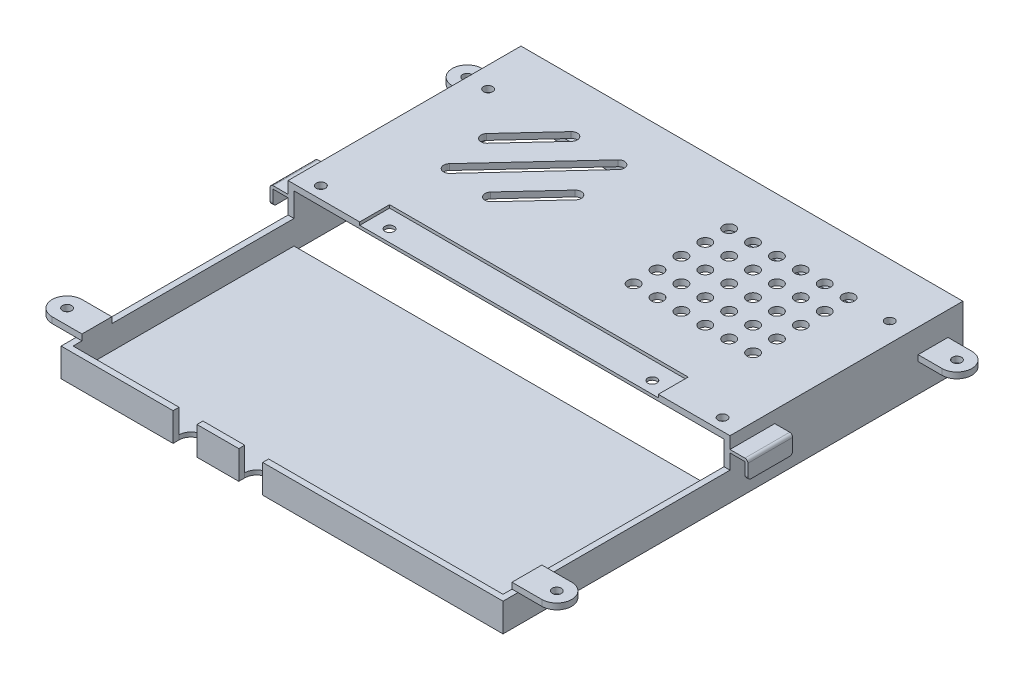
SolidWorks part; units mm, degrees
material "PET"
ref_plane "前视基准面" through (0, 0, 0) normal (0, 0, 1) x (1, 0, 0)
ref_plane "上视基准面" through (0, 0, 0) normal (0, 1, 0) x (1, 0, 0)
ref_plane "右视基准面" through (0, 0, 0) normal (1, 0, 0) x (0, 0, -1)
other "边界框"
ref_plane "Default Plane" through (-13, 0, 0) normal (0, 0, -1) x (-1, 0, 0)
other "Configuration Table"
sketch "草图1" plane through (0, 0, 0) normal (1, 0, 0) x (0, 0, -1)
  line L0 (0, 0) -> (154, 0)
  line L1 (0, 0) -> (0, 9.5)
  line L2 (0, 9.5) -> (76, 9.5)
  line L3 (76, 9.5) -> (76, 19.5)
  line L4 (76, 19.5) -> (154, 19.5)
  line L5 (154, 19.5) -> (154, 0)
  dimension "D1" = 154
  dimension "D2" = 19.5
  dimension "D3" = 9.5
  dimension "D4" = 78
extrude "凸台-拉伸1" add sketch "草图1" along normal blind 148
sketch "草图2" plane through (0, 9.5, 0) normal (0, 1, 0) x (1, 0, 0)
  line L0 (146, 2) -> (2, 2)
  line L1 (2, 2) -> (2, 76)
  line L2 (2, 76) -> (146, 76)
  line L3 (146, 76) -> (146, 2)
  line L4 (148, 76) -> (0, 76) construction
  line L5 (148, 76) -> (148, 0) construction
  line L7 (0, 76) -> (0, 0) construction
  dimension "D1" = 2
  dimension "D2" = 2
  dimension "D3" = 2
extrude "切除-拉伸1" cut sketch "草图2" against normal blind 8 contours L3 L0 L1 L2
sketch "草图3" plane through (0, 0, 0) normal (0, -1, 0) x (1, 0, 0)
  line L0 (146, -152) -> (2, -152)
  line L1 (2, -152) -> (2, -76)
  line L2 (2, -76) -> (146, -76)
  line L3 (146, -76) -> (146, -152)
  line L4 (148, 0) -> (148, -154) construction
  line L5 (148, -154) -> (0, -154) construction
  line L6 (0, 0) -> (0, -154) construction
  dimension "D1" = 2
  dimension "D2" = 2
  dimension "D3" = 2
  dimension "D4" = 78
extrude "切除-拉伸2" cut sketch "草图3" against normal blind 17.5
sketch "草图6" plane through (0, 9.5, 0) normal (0, 1, 0) x (1, 0, 0)
  line L0 (146, 5) -> (156, 5)
  line L1 (148, 0) -> (0, 0) construction
  line L2 (146, 5) -> (146, 15)
  line L3 (146, 76) -> (146, 2) construction
  line L4 (156, 15) -> (146, 15)
  line L5 (74, 2) -> (74, 12.7492) construction
  line L7 (-8, 15) -> (2, 15)
  line L8 (2, 5) -> (2, 15)
  line L9 (2, 5) -> (-8, 5)
  line L11 (146, 139) -> (156, 139)
  line L12 (146, 139) -> (146, 149)
  line L13 (156, 149) -> (146, 149)
  line L14 (146, 76) -> (146, 2) construction
  line L15 (148, 154) -> (0, 154) construction
  line L17 (-8, 149) -> (2, 149)
  line L18 (2, 139) -> (2, 149)
  line L19 (2, 139) -> (-8, 139)
  arc A0 (156, 5) -> (156, 15) centre (156, 10) ccw
  circle A1 centre (156, 10) radius 1.525
  circle A2 centre (-8, 10) radius 1.525
  arc A3 (-8, 5) -> (-8, 15) centre (-8, 10) cw
  arc A4 (156, 139) -> (156, 149) centre (156, 144) ccw
  circle A5 centre (156, 144) radius 1.525
  circle A6 centre (-8, 144) radius 1.525
  arc A7 (-8, 139) -> (-8, 149) centre (-8, 144) cw
  dimension "D5" = 3.05
  dimension "D9" = 3.05
  dimension "D1" = 5
  dimension "D2" = 10
  dimension "D3" = 10
  dimension "D4" = 10
  dimension "D6" = 10
  dimension "D7" = 10
  dimension "D8" = 10
  dimension "D10" = 0
  dimension "D11" = 10
extrude "凸台-拉伸2" add sketch "草图6" along normal blind 2
sketch "草图7" plane through (0, 19.5, 0) normal (0, 1, 0) x (1, 0, 0)
  line L0 (148, 154) -> (148, 76) construction
  line L1 (148, 76) -> (0, 76) construction
  line L2 (0, 154) -> (0, 76) construction
  circle A0 centre (118, 80) radius 1.525
  circle A1 centre (30, 80) radius 1.525
  dimension "D1" = 3.05
  dimension "D4" = 3.05
  dimension "D2" = 30
  dimension "D3" = 4
  dimension "D5" = 30
  dimension "D6" = 4
extrude "切除-拉伸3" cut sketch "草图7" against normal blind 2
sketch "草图8" plane through (0, 19.5, 0) normal (0, 1, 0) x (1, 0, 0)
  line L0 (2, 76) -> (146, 76) construction
  line L1 (24, 76) -> (124, 76)
  line L2 (24, 76) -> (24, 86)
  line L3 (24, 86) -> (124, 86)
  line L4 (124, 76) -> (124, 86)
  line L6 (148, 154) -> (148, 76) construction
  line L7 (0, 154) -> (0, 76) construction
  dimension "D1" = 24
  dimension "D2" = 24
  dimension "D3" = 10
extrude "切除-拉伸4" cut sketch "草图8" against normal blind 1
sketch "草图10" plane through (0, 19.5, 0) normal (0, 1, 0) x (1, 0, 0)
  line L0 (34.6681, 136.223) -> (21.0932, 121.5355) construction
  line L1 (36.1368, 134.8655) -> (22.562, 120.178)
  line L2 (33.1993, 137.5805) -> (19.6245, 122.893)
  line L3 (50.7208, 135.9117) -> (23.5711, 106.5367) construction
  line L4 (52.1896, 134.5543) -> (25.0399, 105.1792)
  line L5 (49.2521, 137.2692) -> (22.1024, 107.8942)
  line L6 (45.1165, 129.8481) -> (37.9715, 122.1174) construction
  line L7 (50.7208, 135.9117) -> (17.7752, 100.2656) construction
  line L8 (52.2931, 119.9332) -> (38.7183, 105.2457) construction
  line L9 (50.8244, 121.2907) -> (37.2495, 106.6031)
  line L10 (53.7619, 118.5757) -> (40.187, 103.8882)
  arc A0 (36.1368, 134.8655) -> (33.1993, 137.5805) centre (34.6681, 136.223) ccw
  arc A1 (19.6245, 122.893) -> (22.562, 120.178) centre (21.0932, 121.5355) ccw
  arc A2 (52.1896, 134.5543) -> (49.2521, 137.2692) centre (50.7208, 135.9117) ccw
  arc A3 (22.1024, 107.8942) -> (25.0399, 105.1792) centre (23.5711, 106.5367) ccw
  arc A4 (50.8244, 121.2907) -> (53.7619, 118.5757) centre (52.2931, 119.9332) cw
  arc A5 (40.187, 103.8882) -> (37.2495, 106.6031) centre (38.7183, 105.2457) cw
  circle A9 centre (92.825, 0) radius 1.5
  circle A10 centre (87.8111, 135.9117) radius 2
  circle A11 centre (95.8111, 135.9117) radius 2
  circle A12 centre (103.8111, 135.9117) radius 2
  circle A13 centre (111.8111, 135.9117) radius 2
  circle A14 centre (119.8111, 135.9117) radius 2
  circle A15 centre (127.8111, 135.9117) radius 2
  circle A16 centre (95.8111, 127.9117) radius 2
  circle A17 centre (103.8111, 127.9117) radius 2
  circle A18 centre (111.8111, 127.9117) radius 2
  circle A19 centre (119.8111, 127.9117) radius 2
  circle A20 centre (127.8111, 127.9117) radius 2
  circle A21 centre (95.8111, 119.9117) radius 2
  circle A22 centre (103.8111, 119.9117) radius 2
  circle A23 centre (111.8111, 119.9117) radius 2
  circle A24 centre (119.8111, 119.9117) radius 2
  circle A25 centre (127.8111, 119.9117) radius 2
  circle A26 centre (95.8111, 111.9117) radius 2
  circle A27 centre (103.8111, 111.9117) radius 2
  circle A28 centre (111.8111, 111.9117) radius 2
  circle A29 centre (119.8111, 111.9117) radius 2
  circle A30 centre (127.8111, 111.9117) radius 2
  circle A31 centre (95.8111, 103.9117) radius 2
  circle A32 centre (103.8111, 103.9117) radius 2
  circle A33 centre (111.8111, 103.9117) radius 2
  circle A34 centre (119.8111, 103.9117) radius 2
  circle A35 centre (127.8111, 103.9117) radius 2
  circle A36 centre (87.8111, 127.9117) radius 2
  circle A37 centre (87.8111, 119.9117) radius 2
  circle A38 centre (87.8111, 111.9117) radius 2
  circle A39 centre (87.8111, 103.9117) radius 2
  point P2 (27.8807, 128.8792)
  point P11 (45.5057, 112.5894)
  point P14 (37.146, 121.2242)
  dimension "D1" = 2
  dimension "D3" = 40
  dimension "D5" = 4
  dimension "D2" = 20
  dimension "D4" = 12
  dimension "D6" = 6
  dimension "D7" = 5
extrude "切除-拉伸6" cut sketch "草图10" against normal blind 2
sketch "草图12" plane through (0, 0, -154) normal (0, 0, -1) x (-1, 0, 0)
  line L0 (-74, 0) -> (-74, 1.6293) construction
  line L8 (-90.7025, 2) -> (-62.0819, 2) construction
  line L11 (-148, 0) -> (0, 0) construction
  line L14 (-145.5, 6.4796) -> (-145.5, 2.6807) construction
  line L17 (-118.5, 7) -> (-118.5, 2)
  line L20 (-148, 9.5) -> (-144.1269, 9.5) construction
  line L23 (-118.5, 7) -> (-75.5, 7)
  line L26 (-75.5, 7) -> (-75.5, 2)
  line L27 (-118.5, 2) -> (-75.5, 2)
  line L29 (-30.5, 8) -> (-5.5, 8)
  line L30 (-30.5, 8) -> (-30.5, 2)
  line L31 (-30.5, 2) -> (-5.5, 2)
  line L32 (-5.5, 8) -> (-5.5, 2)
  dimension "D1" = 2
  dimension "D2" = 71.5
  dimension "D3" = 27
  dimension "D4" = 5
  dimension "D5" = 70
  dimension "D6" = 6
  dimension "D7" = 115
  dimension "D8" = 140
extrude "切除-拉伸7" cut sketch "草图12" against normal blind 2
sketch "草图14" plane through (0, 17.5, 0) normal (0, -1, 0) x (1, 0, 0)
  line L0 (146, -76) -> (2, -76) construction
  line L1 (2.5, -76) -> (145.5, -76) construction
  line L2 (2.5, -76) -> (2.5, -151) construction
  line L3 (2.5, -151) -> (145.5, -151) construction
  line L4 (145.5, -76) -> (145.5, -151) construction
  line L5 (74, -76) -> (74, -82.6616) construction
  circle A0 centre (141.5, -80) radius 1.525
  circle A1 centre (141.5, -136) radius 1.525
  circle A2 centre (7, -136) radius 1.525
  circle A3 centre (7, -80) radius 1.525
  point P7 (74, -76)
  dimension "D5" = 3.05
  dimension "D6" = 4
  dimension "D8" = 15
  dimension "D1" = 143
  dimension "D2" = 75
  dimension "D3" = 4
  dimension "D4" = 4
  dimension "D7" = 15
  dimension "D9" = 4.5
  dimension "D10" = 4.5
  dimension "D11" = 4
extrude "切除-拉伸8" cut sketch "草图14" against normal blind 2
sketch "草图15" plane through (0, 0, -2) normal (0, 0, -1) x (-1, 0, 0)
  line L2 (-74, 9.5) -> (-74, 6.4498) construction
  line L4 (-145.5, 4.6803) -> (-2.5, 4.6803) construction
  line L25 (-37.5, 1.5) -> (-45.5, 1.5)
  line L26 (-37.5, 1.5) -> (-37.5, 9.5)
  line L27 (-37.5, 9.5) -> (-45.5, 9.5)
  line L28 (-45.5, 1.5) -> (-45.5, 9.5)
  line L29 (-59.5, 1.5) -> (-67.5, 1.5)
  line L30 (-59.5, 1.5) -> (-59.5, 9.5)
  line L31 (-59.5, 9.5) -> (-67.5, 9.5)
  line L32 (-67.5, 1.5) -> (-67.5, 9.5)
  point P2 (-45.5, 9.5)
  point P3 (-37.5, 1.5)
  point P7 (-74, 4.6803)
  point P12 (-59.5, 1.5)
  point P13 (-67.5, 9.5)
  dimension "D2" = 143
extrude "切除-拉伸9" cut sketch "草图15" against normal blind 10
sketch "草图16" plane through (0, 1.5, 0) normal (0, 1, 0) x (1, 0, 0)
  line L2 (45.5, 2) -> (45.5, 0)
  line L11 (45.5, 0) -> (37.5, 0)
  line L12 (45.5, 0) -> (37.5, 0) construction
  line L13 (37.5, 0) -> (37.5, 2)
  line L14 (67.5, 2) -> (67.5, 0)
  line L15 (67.5, 0) -> (59.5, 0)
  line L16 (59.5, 0) -> (59.5, 2)
  arc A2 (45.5, 2) -> (37.5, 2) centre (41.5, 2) ccw
  arc A3 (67.5, 2) -> (59.5, 2) centre (63.5, 2) ccw
  point P16 (41.5, 2)
  point P18 (63.5, 2)
  dimension "D1" = 8
  dimension "D2" = 8
extrude "切除-拉伸11" cut sketch "草图16" against normal blind 10
sketch "草图17" plane through (0, 0, -139) normal (0, 0, 1) x (1, 0, 0)
  line L1 (148, 14.5) -> (148, 15.5)
  line L2 (0, 15.5) -> (-6, 15.5)
  line L3 (-6, 15.5) -> (-6, 9.5)
  line L4 (-6, 9.5) -> (-5, 9.5)
  line L5 (153, 14.5) -> (148, 14.5)
  line L6 (-5, 9.5) -> (-5, 14.5)
  line L7 (-5, 14.5) -> (0, 14.5)
  line L10 (0, 14.5) -> (0, 15.5)
  line L11 (153, 9.5) -> (153, 14.5)
  line L12 (154, 9.5) -> (153, 9.5)
  line L13 (0, 19.5) -> (0, 9.5) construction
  line L14 (74, 19.5) -> (74, 17.0177) construction
  line L15 (124, 19.5) -> (24, 19.5) construction
  line L16 (154, 15.5) -> (154, 9.5)
  line L17 (148, 15.5) -> (154, 15.5)
  dimension "D1" = 5
  dimension "D2" = 1
  dimension "D3" = 1
  dimension "D4" = 5
  dimension "D5" = 0
  dimension "D6" = 2.4823
extrude "凸台-拉伸3" add sketch "草图17" along normal blind 15 from offset 48
fillet "圆角1" radius 1 2 edges at (154, 15.5, -83.5) (-6, 15.5, -83.5)
fillet "圆角2" radius 1 4 edges at (-5.5, 9.5, -76) (-5.5, 9.5, -91) (153.5, 9.5, -91) (153.5, 9.5, -76)
